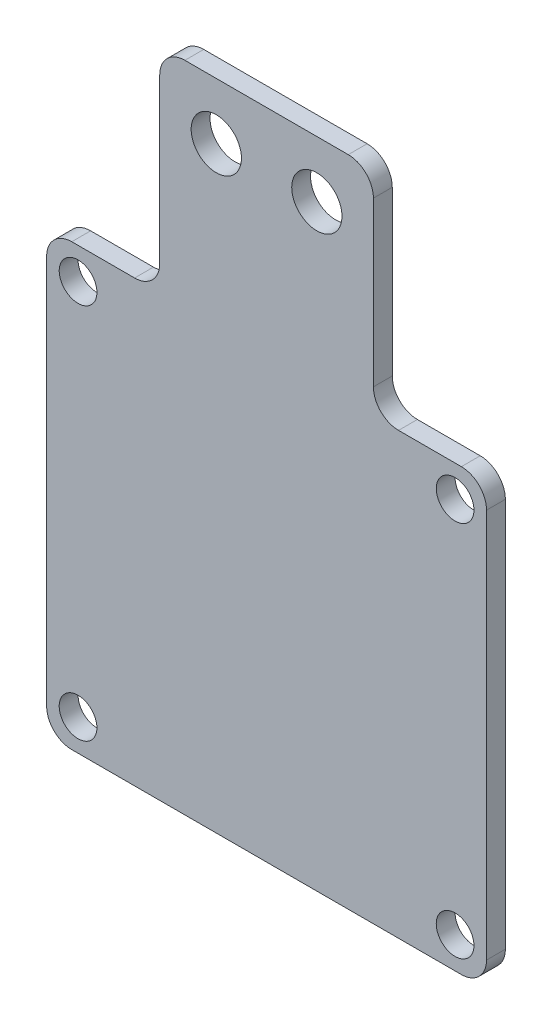
SolidWorks part; units mm, degrees
ref_plane "Alzado" through (0, 0, 0) normal (0, 0, 1) x (1, 0, 0)
ref_plane "Planta" through (0, 0, 0) normal (0, 1, 0) x (1, 0, 0)
ref_plane "Vista lateral" through (0, 0, 0) normal (1, 0, 0) x (0, 0, -1)
sketch "Croquis1" plane through (0, 0, 0) normal (0, 0, 1) x (1, 0, 0)
  line L0 (0, 0) -> (0, 52) construction
  line L1 (0, 0) -> (-15.5, 0)
  line L2 (-17.5, 2) -> (-17.5, 33)
  line L3 (-15.5, 35) -> (-10.5, 35)
  line L4 (-8.5, 37) -> (-8.5, 50)
  line L5 (-6.5, 52) -> (0, 52)
  line L6 (-1, 1) -> (-15.5, 1) construction
  line L7 (-16.5, 2) -> (-16.5, 33) construction
  line L8 (-15.5, 34) -> (-10.5, 34) construction
  line L12 (-6.5, 51) -> (-1, 51) construction
  line L13 (-7.5, 37) -> (-7.5, 50) construction
  line L14 (-1, 1) -> (-1, 51) construction
  line L15 (-8.5, 49.5) -> (-6, 49.5) construction
  line L16 (-6, 49.5) -> (-6, 52) construction
  line L17 (-6, 49.5) -> (-0.2181, 49.5) construction
  line L18 (-6, 49.5) -> (-6, 42.8951) construction
  line L19 (6, 49.5) -> (6, 42.8951) construction
  line L20 (6, 49.5) -> (0.2181, 49.5) construction
  line L21 (6, 49.5) -> (6, 52) construction
  line L22 (8.5, 49.5) -> (6, 49.5) construction
  line L23 (15.5, 34) -> (10.5, 34) construction
  line L24 (16.5, 2) -> (16.5, 33) construction
  line L25 (1, 1) -> (15.5, 1) construction
  line L26 (6.5, 52) -> (0, 52)
  line L27 (8.5, 37) -> (8.5, 50)
  line L28 (15.5, 35) -> (10.5, 35)
  line L29 (17.5, 2) -> (17.5, 33)
  line L30 (0, 0) -> (15.5, 0)
  arc A0 (-8.5, 50) -> (-6.5, 52) centre (-6.5, 50) cw
  arc A1 (-8.5, 37) -> (-10.5, 35) centre (-10.5, 37) cw
  arc A2 (-17.5, 33) -> (-15.5, 35) centre (-15.5, 33) cw
  arc A3 (-15.5, 0) -> (-17.5, 2) centre (-15.5, 2) cw
  arc A4 (-15.5, 1) -> (-16.5, 2) centre (-15.5, 2) cw construction
  arc A5 (-16.5, 33) -> (-15.5, 34) centre (-15.5, 33) cw construction
  circle A8 centre (-15, 2.5) radius 1.5
  circle A9 centre (-15, 32.5) radius 1.5
  arc A10 (-7.5, 37) -> (-10.5, 34) centre (-10.5, 37) cw construction
  arc A11 (-7.5, 50) -> (-6.5, 51) centre (-6.5, 50) cw construction
  circle A12 centre (-4, 47.5) radius 2
  arc A13 (16.5, 33) -> (15.5, 34) centre (15.5, 33) ccw construction
  arc A14 (15.5, 1) -> (16.5, 2) centre (15.5, 2) ccw construction
  circle A15 centre (4, 47.5) radius 2
  circle A16 centre (15, 32.5) radius 1.5
  circle A17 centre (15, 2.5) radius 1.5
  arc A18 (15.5, 0) -> (17.5, 2) centre (15.5, 2) ccw
  arc A19 (17.5, 33) -> (15.5, 35) centre (15.5, 33) ccw
  arc A20 (8.5, 37) -> (10.5, 35) centre (10.5, 37) ccw
  arc A21 (8.5, 50) -> (6.5, 52) centre (6.5, 50) ccw
  point P0 (6, 47.5)
  point P33 (-16.5, 2.5)
  point P34 (-15, 1)
  point P35 (-15, 34)
  point P36 (-16.5, 32.5)
  point P44 (-4, 49.5)
  point P45 (-6, 47.5)
  point P68 (4, 49.5)
  point P81 (16.5, 32.5)
  point P82 (15, 34)
  point P83 (15, 1)
  point P84 (16.5, 2.5)
  dimension "D5" = 2
  dimension "D7" = 2.5
  dimension "D8" = 3
  dimension "D10" = 4
  dimension "D1" = 52
  dimension "D2" = 35
  dimension "D3" = 17
  dimension "D4" = 35
  dimension "D9" = 2.5
  dimension "D6" = 1
extrude "Saliente-Extruir1" add sketch "Croquis1" along normal blind 1.5
